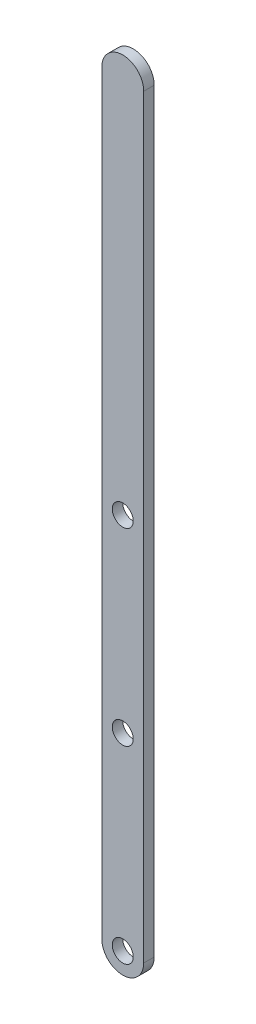
SolidWorks part; units mm, degrees
material "5052-H32"
ref_plane "Front Plane" through (0, 0, 0) normal (0, 0, 1) x (1, 0, 0)
ref_plane "Top Plane" through (0, 0, 0) normal (0, 1, 0) x (1, 0, 0)
ref_plane "Right Plane" through (0, 0, 0) normal (1, 0, 0) x (0, 0, -1)
sketch "Sketch1" plane through (0, 0, 0) normal (0, 0, 1) x (1, 0, 0)
  line L0 (-25.4, -457.2) -> (-25.4, 0)
  line L1 (25.4, 0) -> (25.4, -457.2)
  line L2 (25.4, 0) -> (25.4, 457.2)
  line L3 (0, 0) -> (0, -228.6) construction
  line L4 (-25.4, 0) -> (-25.4, 457.2)
  arc A0 (25.4, 0) -> (-25.4, 0) centre (0, 0) ccw construction
  arc A1 (-25.4, -457.2) -> (25.4, -457.2) centre (0, -457.2) ccw
  circle A2 centre (0, 0) radius 12.7
  circle A3 centre (0, -457.2) radius 12.7
  circle A5 centre (0, -228.6) radius 12.7
  arc A6 (25.4, 457.2) -> (-25.4, 457.2) centre (0, 457.2) ccw
  dimension "D1" = 25.4
  dimension "D3" = 25.4
  dimension "D4" = 25.4
  dimension "D5" = 228.6
  dimension "D2" = 457.2
  dimension "D6" = 457.2
extrude "Boss-Extrude1" add sketch "Sketch1" along normal blind 12.7
sketch "Sketch2" plane through (0, 0, 12.7) normal (0, 0, 1) x (1, 0, 0)
  line L0 (0, -457.2) -> (0, -381) construction
  line L1 (0, -381) -> (0, -304.8) construction
  line L2 (0, -304.8) -> (0, -228.6) construction
  line L3 (0, -228.6) -> (0, -152.4) construction
  line L4 (0, -152.4) -> (0, -76.2) construction
  line L5 (0, -457.2) -> (-263.9645, -609.6) construction
  line L6 (0, -381) -> (-276.2426, -509.814) construction
  line L7 (0, -304.8) -> (-286.4183, -409.0477) construction
  line L8 (0, -228.6) -> (-294.4142, -307.488) construction
  line L9 (0, -152.4) -> (-300.1694, -205.328) construction
  line L10 (0, -76.2) -> (-303.6401, -102.7651) construction
  line L11 (0, -76.2) -> (0, 0) construction
  line L12 (0, 0) -> (0, 76.2) construction
  line L13 (0, 76.2) -> (0, 152.4) construction
  line L14 (0, 152.4) -> (0, 228.6) construction
  line L15 (0, 228.6) -> (0, 304.8) construction
  line L16 (0, 304.8) -> (0, 381) construction
  line L17 (0, 381) -> (0, 457.2) construction
  line L18 (0, 0) -> (-304.8, 0) construction
  line L19 (0, 76.2) -> (-304.6143, 86.8374) construction
  line L20 (0, 152.4) -> (-304.0575, 173.6618) construction
  line L21 (0, 228.6) -> (-303.1303, 260.4603) construction
  line L22 (0, 304.8) -> (-301.8337, 347.22) construction
  line L23 (0, 381) -> (-300.1694, 433.928) construction
  line L24 (0, 457.2) -> (-298.1394, 520.5715) construction
  point P23 (0, 0)
  point P28 (-304.8, 115.3003)
  point P29 (-303.6126, 188.088)
  point P30 (-301.8337, 381)
  point P31 (-301.3502, 431.3251)
  point P32 (-294.4142, 539.0191)
  dimension "D1" = 76.2
  dimension "D2" = 304.8
  dimension "D3" = 5
  dimension "D4" = 120
  dimension "D5" = 5
  dimension "D6" = 5
  dimension "D7" = 5
  dimension "D8" = 5
  dimension "D9" = 5
  dimension "D10" = 2
  dimension "D11" = 2
  dimension "D12" = 2
  dimension "D13" = 2
  dimension "D14" = 2
  dimension "D15" = 2
